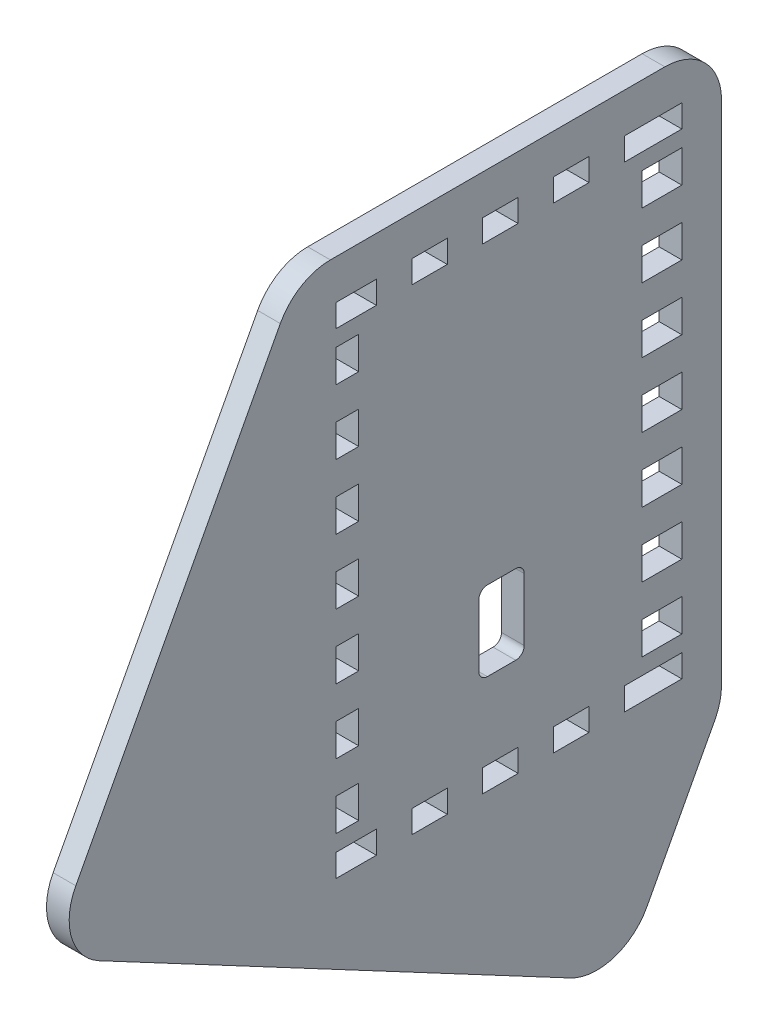
SolidWorks part; units mm, degrees
ref_plane "Piano frontale" through (0, 0, 0) normal (0, 0, 1) x (1, 0, 0)
ref_plane "Piano superiore" through (0, 0, 0) normal (0, 1, 0) x (1, 0, 0)
ref_plane "Piano destro" through (0, 0, 0) normal (1, 0, 0) x (0, 0, -1)
sketch "Schizzo1" plane through (0, 0, 0) normal (1, 0, 0) x (0, 0, -1)
  line L1 (0, 0) -> (50, 0)
  line L2 (0, 0) -> (0, 80)
  line L3 (0, 80) -> (50, 80)
  line L4 (50, 0) -> (50, 80)
  dimension "D1" = 80
  dimension "D2" = 50
extrude "Estrusione-Estrusione1" add sketch "Schizzo1" along normal blind 4
sketch "Schizzo2" plane through (4, 0, 0) normal (1, 0, 0) x (0, 0, -1)
  line L0 (0, 80) -> (0, 0) construction
  line L1 (0, 77.1429) -> (-4, 77.1429)
  line L2 (0, 77.1429) -> (0, 80)
  line L3 (0, 80) -> (-4, 80)
  line L4 (-4, 77.1429) -> (-4, 80)
  line L6 (50, 80) -> (57, 80)
  line L7 (50, 80) -> (50, 77.1429)
  line L8 (50, 77.1429) -> (57, 77.1429)
  line L9 (57, 80) -> (57, 77.1429)
  line L10 (50, 0) -> (57, 0)
  line L11 (50, 0) -> (50, 2.8571)
  line L12 (50, 2.8571) -> (57, 2.8571)
  line L13 (57, 0) -> (57, 2.8571)
  line L14 (0, 0) -> (-4, 0)
  line L15 (0, 0) -> (0, 2.8571)
  line L16 (0, 2.8571) -> (-4, 2.8571)
  line L17 (-4, 0) -> (-4, 2.8571)
  dimension "D1" = 4
  dimension "D2" = 7
  dimension "D3" = 2.8571
  dimension "D4" = 2.8571
extrude "Estrusione-Estrusione2" add sketch "Schizzo2" against normal blind 4
sketch "Schizzo3" plane through (4, 0, 0) normal (1, 0, 0) x (0, 0, -1)
  line L0 (0, 77.1429) -> (0, 2.8571) construction
  line L1 (0, 71.4286) -> (-4, 71.4286)
  line L2 (0, 71.4286) -> (0, 65.7143)
  line L3 (0, 65.7143) -> (-4, 65.7143)
  line L4 (-4, 71.4286) -> (-4, 65.7143)
  line L5 (50, 2.8571) -> (50, 77.1429) construction
  line L6 (50, 71.4286) -> (57, 71.4286)
  line L7 (50, 71.4286) -> (50, 65.7143)
  line L8 (50, 65.7143) -> (57, 65.7143)
  line L9 (57, 71.4286) -> (57, 65.7143)
  line L10 (-4, 77.1429) -> (0, 77.1429) construction
  line L11 (-4, 80) -> (-4, 77.1429) construction
  line L12 (57, 77.1429) -> (57, 80) construction
  dimension "D1" = 5.7143
  dimension "D2" = 5.7143
extrude "Estrusione-Estrusione3" add sketch "Schizzo3" against normal blind 4
pattern_linear "Ripetizione a L1" count 6 spacing 11.4286 along (0, -1, 0) of "Estrusione-Estrusione3"
sketch "Schizzo4" plane through (4, 0, 0) normal (1, 0, 0) x (0, 0, -1)
  line L0 (57, 80) -> (-4, 80) construction
  line L1 (3.125, 80) -> (9.375, 80)
  line L2 (3.125, 80) -> (3.125, 84)
  line L3 (3.125, 84) -> (9.375, 84)
  line L4 (9.375, 80) -> (9.375, 84)
  line L5 (-4, 0) -> (57, 0) construction
  line L6 (3.125, 0) -> (9.375, 0)
  line L7 (3.125, 0) -> (3.125, -4)
  line L8 (3.125, -4) -> (9.375, -4)
  line L9 (9.375, 0) -> (9.375, -4)
  line L10 (0, 77.1429) -> (0, 71.4286) construction
  point P14 (6.25, 0)
  dimension "D1" = 3.125
  dimension "D2" = 6.25
  dimension "D3" = 4
  dimension "D4" = 4
extrude "Estrusione-Estrusione4" add sketch "Schizzo4" against normal blind 4
pattern_linear "Ripetizione a L2" count 4 spacing 12.5 along (0, 0, -1) of "Estrusione-Estrusione4"
sketch "Schizzo5" plane through (4, 0, 0) normal (1, 0, 0) x (0, 0, -1)
  line L1 (64, -11) -> (46.1601, -44.552)
  line L2 (46.1601, -44.552) -> (-54.5906, 9.0181)
  line L3 (-54.5906, 9.0181) -> (-11, 91)
  line L9 (-11, 91) -> (64, 91)
  line L10 (64, 91) -> (64, -11)
  line L11 (-4, 84) -> (57, 84)
  line L12 (57, 84) -> (57, -4)
  line L13 (9.375, 84) -> (3.125, 84) construction
  line L14 (57, 65.7143) -> (57, 71.4286) construction
  line L18 (-4, 84) -> (-4, -4)
  line L19 (-4, 60) -> (-4, 54.2857) construction
  line L20 (57, -4) -> (-4, -4)
  line L21 (28.125, -4) -> (34.375, -4) construction
  dimension "D1" = 7
  dimension "D2" = 7
  dimension "D3" = 7
  dimension "D4" = 38
  dimension "D5" = 7
  dimension "D6" = 62
extrude "Estrusione-Estrusione5" add sketch "Schizzo5" against normal blind 4
fillet "Raccordo1" radius 10 2 edges at (2, -44.552, -46.1601) (2, 9.0181, 54.5906)
sketch "Schizzo6" plane through (4, 0, 0) normal (1, 0, 0) x (0, 0, -1)
  line L0 (21.2, 26) -> (21.2, 15)
  line L5 (22.7, 27.5) -> (27.7, 27.5)
  line L6 (29.2, 26) -> (29.2, 15)
  line L7 (22.7, 13.5) -> (27.7, 13.5)
  line L8 (0, 20) -> (0, 14.2857) construction
  line L9 (21.875, 0) -> (28.125, 0) construction
  arc A0 (21.2, 26) -> (22.7, 27.5) centre (22.7, 26) cw
  arc A1 (27.7, 27.5) -> (29.2, 26) centre (27.7, 26) cw
  arc A2 (29.2, 15) -> (27.7, 13.5) centre (27.7, 15) cw
  arc A3 (21.2, 15) -> (22.7, 13.5) centre (22.7, 15) ccw
  dimension "D1" = 1.5
  dimension "D2" = 14
  dimension "D3" = 8
  dimension "D4" = 1.5
  dimension "D5" = 1.5
  dimension "D6" = 1.5
  dimension "D7" = 21.2
  dimension "D8" = 13.5
extrude "Taglio-Estrusione1" cut sketch "Schizzo6" against normal through all and the other way through all
fillet "Raccordo2" radius 10 3 edges at (2, -11, -64) (2, 91, -64) (2, 91, 11)
equation "\"WFront\"= 140mm"
equation "\"HFront\"= 80mm"
equation "\"DFront\"= 4mm"
equation "\"WLeft\"= 50mm"
equation "\"HLeft\"= 80mm"
equation "\"DLeft\"= 4mm"
equation "\"WTop\"= 140mm"
equation "\"HTop\"= 50mm"
equation "\"DTop\"= 4mm"
equation "\"N_Denti_W\"= 10"
equation "\"N_Denti_H\"= 7"
equation "\"N_Denti_D\"= 4"
equation "\"HDistDenti\"= \"HFront\" / \"N_Denti_H\""
equation "\"WDistDenti\"= \"WFront\" / \"N_Denti_W\""
equation "\"DDistDenti\"= \"WLeft\" / \"N_Denti_D\""
equation "\"HDenti\"= \"HDistDenti\" / 2"
equation "\"WDenti\"= \"WDistDenti\" / 2"
equation "\"DDenti\"= \"DDistDenti\" / 2"
equation "\"WDisplay\"= 95mm"
equation "\"HDisplay\"= 61mm"
equation "\"CEnc\"= 7mm"
equation "\"Display_to_Enc_W\"= 11.5 + \"CEnc\" / 2"
equation "\"Display_to_Dx\"= 32mm"
equation "\"Display_to_Top\"= 10mm"
equation "\"Display_to_Enc_H\"= 24 + \"CEnc\" / 2"
equation "\"D1@Schizzo1\"=\"HLeft\""
equation "\"D2@Schizzo1\"=\"WLeft\""
equation "\"D1@Estrusione-Estrusione1\"=\"DLeft\""
equation "\"D1@Schizzo2\"=\"DFront\""
equation "\"D2@Schizzo2\"=\"DFront\"+\"DMask\""
equation "\"D3@Schizzo2\"=\"HDenti\"/2"
equation "\"D4@Schizzo2\"=\"HDenti\"/2 "
equation "\"D1@Estrusione-Estrusione2\"=\"DLeft\""
equation "\"D1@Schizzo3\"=\"HDenti\""
equation "\"D2@Schizzo3\"=\"HDenti\""
equation "\"D1@Estrusione-Estrusione3\"=\"DLeft\""
equation "\"D1@Ripetizione a L1\"=\"N_Denti_H\"-1"
equation "\"D1@Schizzo4\"=\"DDenti\"/2"
equation "\"D2@Schizzo4\"=\"DDenti\""
equation "\"D3@Schizzo4\"=\"DTop\""
equation "\"D4@Schizzo4\"=\"DTop\""
equation "\"D1@Estrusione-Estrusione4\"=\"DLeft\""
equation "\"D3@Ripetizione a L2\"=\"DDistDenti\""
equation "\"D1@Ripetizione a L2\"=\"N_Denti_D\""
equation "\"D1@Estrusione-Estrusione5\"=\"DLeft\""
equation "\"DMask\"= 3mm"
